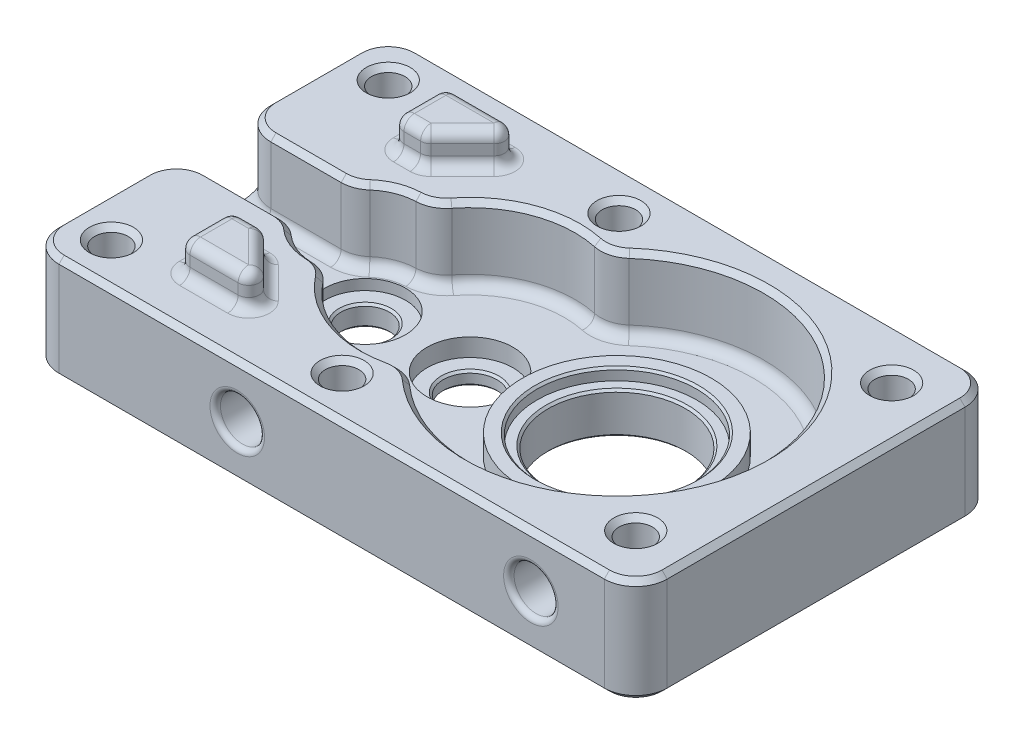
SolidWorks part; units mm, degrees
ref_plane "Front Plane" through (0, 0, 0) normal (0, 0, 1) x (1, 0, 0)
ref_plane "Top Plane" through (0, 0, 0) normal (0, 1, 0) x (1, 0, 0)
ref_plane "Right Plane" through (0, 0, 0) normal (1, 0, 0) x (0, 0, -1)
sketch "Sketch1" plane through (0, 28, 0) normal (0, 1, 0) x (1, 0, 0)
  line L1 (43, -17.2) -> (-15, -17.2)
  line L2 (43, -17.2) -> (43, 17.2)
  line L3 (43, 17.2) -> (-15, 17.2)
  line L4 (-15, -17.2) -> (-15, 17.2)
  circle A0 centre (0, 0) radius 14 construction
  circle A1 centre (0, 0) radius 2.5 construction
  circle A2 centre (10, 0) radius 7.5 construction
  circle A3 centre (10, 0) radius 2.5 construction
  circle A4 centre (24, 0) radius 11.5 construction
  circle A5 centre (24, 0) radius 3 construction
  circle A6 centre (24, 0) radius 6.5 construction
  point P4 (-15, 0)
  dimension "D4" = 28
  dimension "D5" = 5
  dimension "D6" = 15
  dimension "D7" = 5
  dimension "D8" = 23
  dimension "D9" = 6
  dimension "D10" = 13
  dimension "D1" = 34.4
  dimension "D2" = 58
  dimension "D3" = 15
extrude "Boss-Extrude1" add sketch "Sketch1" along normal blind 3 contours L4 L3 L2 L1
sketch "Sketch2" plane through (0, 28, 0) normal (0, -1, 0) x (1, 0, 0)
  circle A0 centre (0, 0) radius 3.85
  dimension "D1" = 7.7
extrude "Cut-Extrude1" cut sketch "Sketch2" along normal blind 1 from surface at -3 starting at face at (14, 31, 0)
sketch "Sketch3" plane through (0, 30, 0) normal (0, 1, 0) x (-1, 0, 0)
  circle A0 centre (0, 0) radius 2.3
  dimension "D1" = 4.6
extrude "Cut-Extrude2" cut sketch "Sketch3" against normal through all
sketch "Sketch4" plane through (0, 31, 0) normal (0, 1, 0) x (1, 0, 0)
  line L4 (-15, -17.2) -> (43, -17.2)
  line L5 (43, -17.2) -> (43, 17.2)
  line L6 (43, 17.2) -> (-15, 17.2)
  line L7 (-15, 17.2) -> (-15, -17.2)
  line L8 (-15, -17.2) -> (43, -17.2)
  line L9 (43, -17.2) -> (43, 17.2)
  line L10 (43, 17.2) -> (-15, 17.2)
  line L11 (-15, 17.2) -> (-15, -17.2)
  arc A0 (1.25, 4.8412) -> (1.25, -4.8412) centre (0, 0) ccw
  arc A1 (1.25, -4.8412) -> (13.5714, -9.3405) centre (10, 0) ccw
  arc A2 (13.5714, -9.3405) -> (13.5714, 9.3405) centre (24, 0) ccw
  arc A3 (13.5714, 9.3405) -> (1.25, 4.8412) centre (10, 0) ccw
  dimension "D1" = 10
  dimension "D2" = 20
  dimension "D3" = 28
  dimension "D4" = 0
extrude "Boss-Extrude2" add sketch "Sketch4" along normal blind 7
sketch "Sketch5" plane through (0, 38, 0) normal (0, 1, 0) x (1, 0, 0)
  line L0 (-4, 3) -> (-4, -3)
  line L1 (-4, 3) -> (-15, 3)
  line L2 (-4, -3) -> (-15, -3)
  line L3 (-15, 3) -> (-15, -3)
  line L4 (-15, -17.2) -> (-15, 17.2) construction
  arc A0 (1.25, 4.8412) -> (1.25, -4.8412) centre (0, 0) ccw construction
  dimension "D1" = 6
extrude "Cut-Extrude3" cut sketch "Sketch5" against normal blind 7
sketch "Sketch6" plane through (0, 28, 0) normal (0, -1, 0) x (1, 0, 0)
  circle A0 centre (10, 0) radius 4.1
  dimension "D1" = 8.2
extrude "Cut-Extrude4" cut sketch "Sketch6" along normal blind 1.7 from surface at -3 starting at face at (0, 31, -3.85)
sketch "Sketch7" plane through (0, 29.3, 0) normal (0, 1, 0) x (-1, 0, 0)
  circle A0 centre (-10, 0) radius 2.55
  circle A1 centre (-10, 0) radius 4.1 construction
  dimension "D1" = 5.1
extrude "Cut-Extrude5" cut sketch "Sketch7" against normal through all
sketch "Sketch14" plane through (0, 31, 0) normal (0, 1, 0) x (1, 0, 0)
  circle A0 centre (24, 0) radius 9
  dimension "D1" = 18
extrude "Boss-Extrude4" add sketch "Sketch14" along normal blind 2
sketch "Sketch15" plane through (0, 33, 0) normal (0, 1, 0) x (1, 0, 0)
  circle A0 centre (24, 0) radius 6.55
  dimension "D1" = 13.1
extrude "Cut-Extrude11" cut sketch "Sketch15" against normal through all
sketch "Sketch16" plane through (0, 33, 0) normal (0, 1, 0) x (1, 0, 0)
  circle A0 centre (24, 0) radius 7.6
  dimension "D1" = 15.2
extrude "Cut-Extrude12" cut sketch "Sketch16" against normal blind 1.1
fillet "Fillet1" radius 3 4 edges at (-15, 33, 17.2) (43, 33, 17.2) (43, 33, -17.2) (-15, 33, -17.2)
fillet "Fillet2" radius 3 8 edges at (13.5714, 34.5, 9.3405) (1.25, 34.5, 4.8412) (-4, 34.5, 3) (-4, 34.5, -3) (13.5714, 34.5, -9.3405) (1.25, 34.5, -4.8412) (-15, 34.5, 3) (-15, 34.5, -3)
fillet "Fillet3" radius 1 15 edges at (-14.1213, 31, 3.8787) (-8.6458, 31, 3) (-4.2308, 31, 3.1938) (-1.8406, 31, 4.6489) (1.1081, 31, 5.3211) (6.5806, 31, 9.3972) (13.4792, 31, 9.8126) (38, 31, 0) (13.4792, 31, -9.8126) (6.5806, 31, -9.3972) (1.1081, 31, -5.3211) (-1.8406, 31, -4.6489) (-4.2308, 31, -3.1938) (-14.1213, 31, -3.8787) (-8.6458, 31, -3)
sketch "Sketch10" plane through (0, 28, 0) normal (0, -1, 0) x (1, 0, 0)
  circle A0 centre (-11, -13.2) radius 1.6
  circle A1 centre (-11, -13.2) radius 2.1 construction
  circle A2 centre (11, -13.2) radius 1.6
  circle A3 centre (-11, 13.2) radius 1.6
  circle A4 centre (11, 13.2) radius 1.6
  circle A5 centre (11, 13.2) radius 2.1 construction
  dimension "D1" = 3.2
extrude "Cut-Extrude8" cut sketch "Sketch10" against normal through all
sketch "Sketch11" plane through (0, 28, 0) normal (0, -1, 0) x (1, 0, 0)
  line L0 (40, -17.2) -> (-12, -17.2) construction
  line L1 (43, 14.2) -> (43, -14.2) construction
  circle A0 centre (38, -12.2) radius 1.6
  dimension "D1" = 3.2
  dimension "D2" = 5
  dimension "D3" = 5
extrude "Cut-Extrude9" cut sketch "Sketch11" against normal through all
sketch "Sketch12" plane through (0, 28, 0) normal (0, -1, 0) x (1, 0, 0)
  circle A0 centre (38, -12.2) radius 2.1
  dimension "D1" = 4.2
extrude "Cut-Extrude10" cut sketch "Sketch12" against normal blind 5
mirror "Mirror1" about plane through (0, 0, 0) normal (0, 0, 1) of "Cut-Extrude10", "Cut-Extrude9"
sketch "Sketch13" plane through (0, 38, 0) normal (0, 1, 0) x (1, 0, 0)
  line L0 (3, -12.7) -> (-5, -12.7)
  line L1 (-5, -12.7) -> (-5, -7.7)
  line L2 (-5, -7.7) -> (-2, -7.7)
  line L3 (-2, -7.7) -> (3, -12.7)
  line L4 (-12, -17.2) -> (40, -17.2) construction
  line L5 (-15, -6) -> (-15, -14.2) construction
  dimension "D1" = 45
  dimension "D2" = 4.5
  dimension "D3" = 10
  dimension "D4" = 8
  dimension "D5" = 5
extrude "Boss-Extrude3" add sketch "Sketch13" along normal blind 3
fillet "Fillet4" radius 1 8 edges at (-1, 41, 12.7) (-5, 41, 10.2) (-3.5, 41, 7.7) (0.5, 41, 10.2) (-2, 39.5, 7.7) (-5, 39.5, 7.7) (-5, 39.5, 12.7) (3, 39.5, 12.7)
fillet "Fillet5" radius 1 8 edges at (-4.7071, 38, 12.4071) (-5, 38, 10.2) (-4.7071, 38, 7.9929) (-3.2071, 38, 7.7) (-2.0315, 38, 7.7761) (-0.2071, 38, 9.4929) (1.5097, 38, 12.0827) (-1.7071, 38, 12.7)
mirror "Mirror2" about plane through (0, 0, 0) normal (0, 0, 1) of "Fillet5", "Fillet4", "Boss-Extrude3"
sketch "Sketch18" plane through (0, 0, -17.2) normal (0, 0, -1) x (-1, 0, 0)
  line L0 (-33, 38) -> (-33, 28) construction
  line L1 (-40, 38) -> (12, 38) construction
  line L2 (-40, 28) -> (12, 28) construction
  line L3 (-43, 28) -> (-43, 38) construction
  circle A0 centre (-33, 33) radius 2.1
  point P8 (-33, 33)
  dimension "D1" = 4.2
  dimension "D2" = 10
extrude "Cut-Extrude14" cut sketch "Sketch18" against normal blind 5
mirror "Mirror3" about plane through (0, 0, 0) normal (0, 0, 1) of "Cut-Extrude14"
pattern_linear "LPattern1" count 2 spacing 28 along (-1, 0, 0) of "Mirror3", "Cut-Extrude14"
fillet "Fillet6" radius 0.5 4 edges at (30.9, 33, 17.2) (2.9, 33, 17.2) (2.9, 33, -17.2) (30.9, 33, -17.2)
chamfer "Chamfer2" distance 0.5 angle 45 38 edges at (14, 28, 17.2) (42.1213, 28, 16.3213) (-14.1213, 28, 16.3213) (43, 28, 0) (-15, 28, 0) (42.1213, 28, -16.3213) (-14.1213, 28, -16.3213) (14, 28, -17.2) (-11, 38, 11.6) (11, 38, 11.6) (38, 38, 13.8) (38, 38, -13.8) (11, 38, -14.8) (-11, 38, -14.8) (-8.6458, 38, 3) (-4.2308, 38, 3.1938) (-14.1213, 38, 3.8787) (-1.8406, 38, 4.6489) (-15, 38, 10.1) (1.1081, 38, 5.3211) (-14.1213, 38, 16.3213) (6.5806, 38, 9.3972) (14, 38, 17.2) (13.4792, 38, 9.8126) (42.1213, 38, 16.3213) (38, 38, 0) (43, 38, 0) (13.4792, 38, -9.8126) (42.1213, 38, -16.3213) (6.5806, 38, -9.3972) (14, 38, -17.2) (1.1081, 38, -5.3211) (-14.1213, 38, -16.3213) (-1.8406, 38, -4.6489) (-15, 38, -10.1) (-4.2308, 38, -3.1938) (-14.1213, 38, -3.8787) (-8.6458, 38, -3)
chamfer "Chamfer3" distance 0.2 angle 45 13 edges at (-11, 28, -14.8) (11, 28, -14.8) (38, 28, 14.3) (38, 28, -14.3) (11, 28, 11.6) (0, 28, 2.3) (10, 28, 2.55) (24, 28, 6.55) (24, 33, 7.6) (24, 31.9, 6.55) (0, 30, 2.3) (10, 29.3, 2.55) (-11, 28, 11.6)
